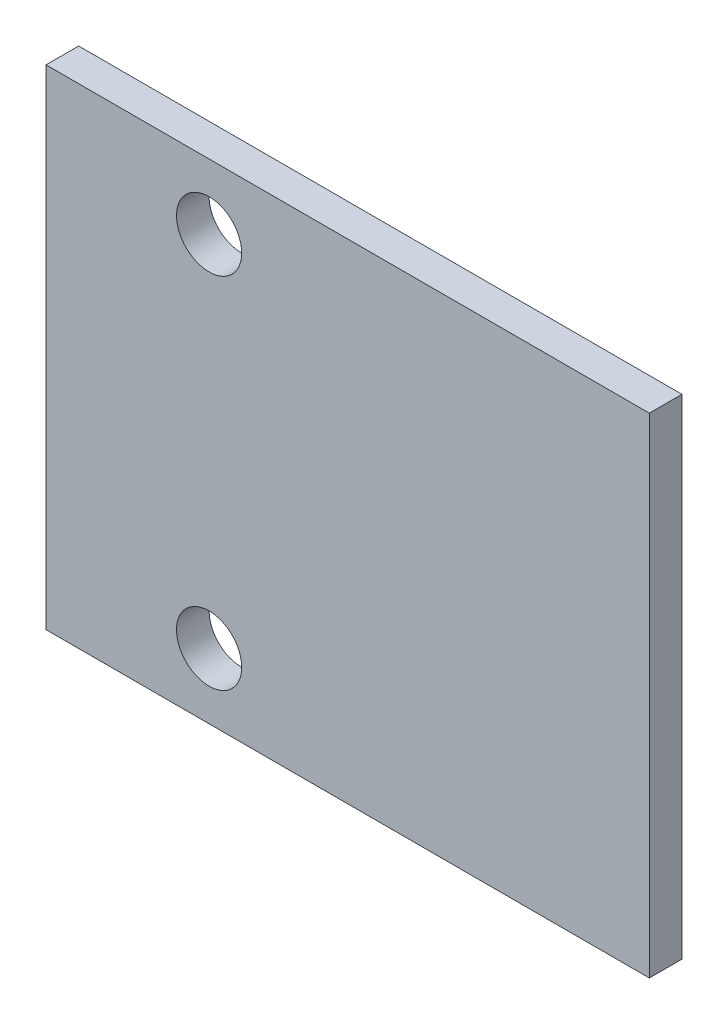
SolidWorks part; units mm, degrees
material "E-Glass Fiber"
ref_plane "Front Plane" through (0, 0, 0) normal (0, 0, 1) x (1, 0, 0)
ref_plane "Top Plane" through (0, 0, 0) normal (0, 1, 0) x (1, 0, 0)
ref_plane "Right Plane" through (0, 0, 0) normal (1, 0, 0) x (0, 0, -1)
sketch "PCB" plane through (0, 0, 0) normal (0, 0, 1) x (1, 0, 0)
  line L0 (-4.25, 7.5) -> (-4.25, -7.5) construction
  line L1 (-9.25, 7.5) -> (9.25, 7.5)
  line L2 (-9.25, 7.5) -> (-9.25, -7.5)
  line L3 (-9.25, -7.5) -> (9.25, -7.5)
  line L4 (9.25, 7.5) -> (9.25, -7.5)
  line L5 (0, -7.5) -> (0, 7.5) construction
  line L6 (-9.25, 0) -> (9.25, 0) construction
  circle A0 centre (-4.25, 5.5) radius 1
  circle A1 centre (-4.25, -5.5) radius 1
  point P0 (0, 0)
  dimension "D4" = 2
  dimension "D1" = 18.5
  dimension "D2" = 15
  dimension "D3" = 11
  dimension "D5" = 5
extrude "Boss-Extrude1" add sketch "PCB" along normal blind 1
